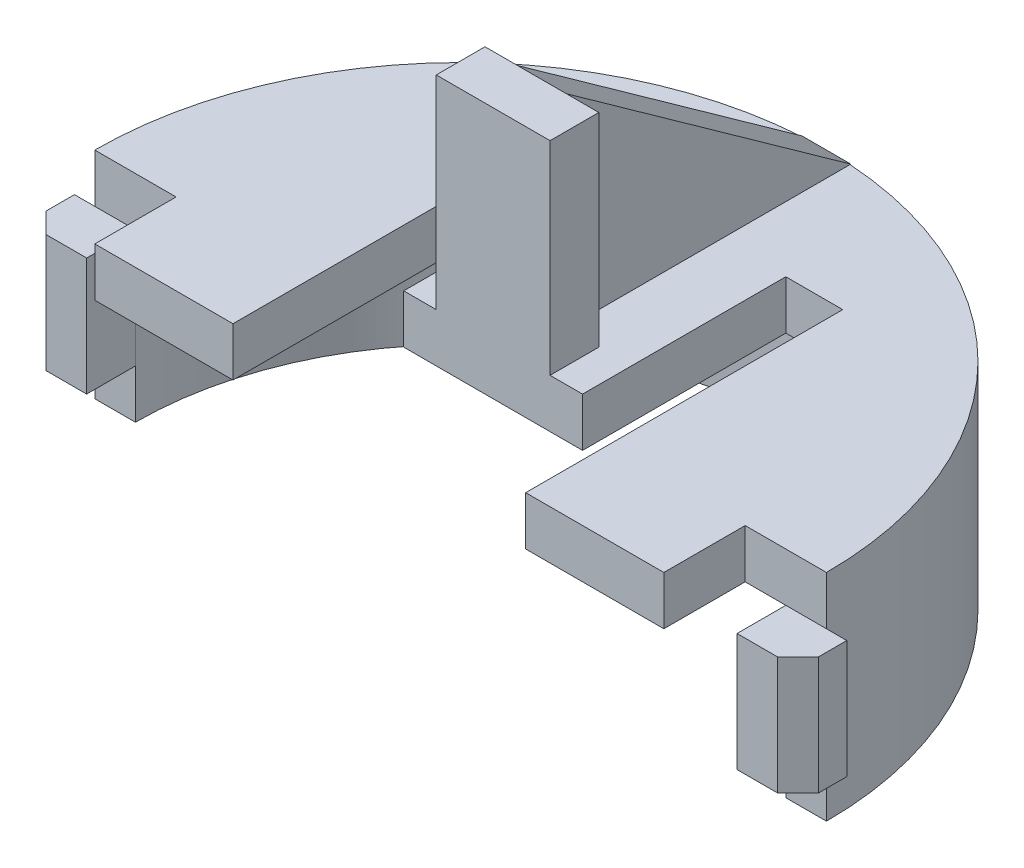
SolidWorks part; units mm, degrees
ref_plane "Front Plane" through (0, 0, 0) normal (0, 0, 1) x (1, 0, 0)
ref_plane "Top Plane" through (0, 0, 0) normal (0, 1, 0) x (1, 0, 0)
ref_plane "Right Plane" through (0, 0, 0) normal (1, 0, 0) x (0, 0, -1)
sketch "Sketch1" plane through (0, 0, 0) normal (0, 0, 1) x (1, 0, 0)
  line L0 (0, 0) -> (9, 0)
  line L1 (9, 0) -> (9, 5.3)
  line L2 (9, 5.3) -> (8, 5.3)
  line L3 (8, 5.3) -> (8, 0)
  line L4 (9, 4.1) -> (0, 4.1)
  line L5 (0, 4.1) -> (0, 5.3)
  line L6 (0, 5.3) -> (8, 5.3)
  line L7 (0, 0) -> (0, 2.65) construction
  dimension "D1" = 9
  dimension "D2" = 5.3
  dimension "D3" = 1
  dimension "D4" = 1.2
revolve "Revolve1" add sketch "Sketch1" angle 180 about L7
sketch "Sketch2" plane through (0, 0, 0) normal (0, 0, 1) x (1, 0, 0)
  line L0 (-8, 4.1) -> (8, 4.1) construction
  line L1 (-3.105, 4.1) -> (3.105, 4.1)
  line L2 (-3.105, 4.1) -> (-3.105, 2.6)
  line L3 (-3.105, 2.6) -> (3.105, 2.6)
  line L4 (3.105, 4.1) -> (3.105, 2.6)
  line L5 (-3.105, 4.1) -> (3.105, 2.6) construction
  line L6 (-3.105, 2.6) -> (3.105, 4.1) construction
  point P0 (0, 3.35)
  dimension "D1" = 6.21
  dimension "D2" = 1.5
  dimension "D3" = 0
  dimension "D4" = 0
extrude "Cut-Extrude1" cut sketch "Sketch2" against normal through all
sketch "Sketch3" plane through (0, 5.3, 0) normal (0, 1, 0) x (1, 0, 0)
  line L0 (9, 0) -> (-9, 0) construction
  line L1 (-3.6, 5.8) -> (3.6, 5.8)
  line L2 (-3.6, 5.8) -> (-3.6, 0)
  line L3 (-3.6, 0) -> (3.6, 0)
  line L4 (3.6, 5.8) -> (3.6, 0)
  line L5 (-3.6, 5.8) -> (3.6, 0) construction
  line L6 (-3.6, 0) -> (3.6, 5.8) construction
  line L8 (-2.2, 5.8) -> (2.2, 5.8)
  line L9 (-2.2, 5.8) -> (-2.2, 0.8)
  line L10 (-2.2, 0.8) -> (2.2, 0.8)
  line L11 (2.2, 5.8) -> (2.2, 0.8)
  line L12 (-2.2, 5.8) -> (2.2, 0.8) construction
  line L13 (-2.2, 0.8) -> (2.2, 5.8) construction
  point P0 (0, 2.9)
  point P8 (0, 3.3)
  line M9 (-9, 0) -> (9, 0)
  dimension "D1" = 7.2
  dimension "D2" = 5.8
  dimension "D3" = 0
  dimension "D4" = 0
  dimension "D5" = 4.4
  dimension "D6" = 5
  dimension "D7" = 0
  dimension "D8" = 0
extrude "Cut-Extrude2" cut sketch "Sketch3" against normal through all contours L1 L11 L10 L9 L2 L4 M9
sketch "Sketch4" plane through (0, 5.3, 0) normal (0, 1, 0) x (1, 0, 0)
  line L1 (3.6, 0) -> (7, 0)
  line L2 (3.6, 0) -> (3.6, -2)
  line L3 (3.6, -2) -> (7, -2)
  line L4 (7, 0) -> (7, -2)
  line L5 (-3.6, 0) -> (-7, 0)
  line L6 (-3.6, 0) -> (-3.6, -2)
  line L7 (-3.6, -2) -> (-7, -2)
  line L8 (-7, 0) -> (-7, -2)
  dimension "D1" = 3.4
  dimension "D2" = 3.4
  dimension "D3" = 2
  dimension "D4" = 2
extrude "Boss-Extrude1" add sketch "Sketch4" against normal blind 1.2
ref_plane "Plane1" through (8, 0, 0) normal (1, 0, 0) x (0, 0, -1)
sketch "Sketch5" plane through (8, 0, 0) normal (1, 0, 0) x (0, 0, -1)
  line L0 (0, 0) -> (0, 5.3) construction
  line L1 (0, 4.1) -> (-1.2, 4.1)
  line L2 (0, 4.1) -> (0, 1.2)
  line L3 (0, 1.2) -> (-1.2, 1.2)
  line L4 (-1.2, 4.1) -> (-1.2, 1.2)
  line L5 (-1.2, 4.1) -> (0, 1.2) construction
  line L6 (0, 4.1) -> (-1.2, 1.2) construction
  point P6 (-0.6, 2.65)
  dimension "D1" = 2.65
  dimension "D2" = 2.9
  dimension "D3" = 1.2
extrude "Boss-Extrude2" add sketch "Sketch5" along normal blind 1.5
chamfer "Chamfer1" distance 0.5 angle 45 1 edges at (9.5, 2.65, 1.2)
mirror "Mirror2" about plane through (0, 0, 0) normal (1, 0, 0) of "Boss-Extrude2", "Chamfer1"
sketch "Sketch6" plane through (0, 0, -0.8) normal (0, 0, 1) x (1, 0, 0)
  line L0 (-2.2, 5.3) -> (2.2, 5.3) construction
  line L1 (1.4, 5.3) -> (-1.4, 5.3)
  line L2 (1.4, 5.3) -> (1.4, 10.3)
  line L3 (1.4, 10.3) -> (-1.4, 10.3)
  line L4 (-1.4, 5.3) -> (-1.4, 10.3)
  line L5 (-1.4, 10.3) -> (1.4, 5.3) construction
  line L6 (-1.4, 5.3) -> (1.4, 10.3) construction
  point P6 (0, 7.8)
  dimension "D1" = 0
  dimension "D2" = 5
  dimension "D3" = 2.8
extrude "Boss-Extrude3" add sketch "Sketch6" against normal blind 1.2 contours L4 L3 L2 L1
sketch "Sketch7" plane through (0, 0, 0) normal (1, 0, 0) x (0, 0, -1)
  line L0 (2, 10.3) -> (9, 5.3)
  line L1 (9, 5.3) -> (0, 5.3) construction
  line L2 (9, 5.3) -> (2, 5.3)
  line L3 (2, 5.3) -> (2, 10.3)
extrude "Boss-Extrude4" add sketch "Sketch7" along normal mid plane 1.2
